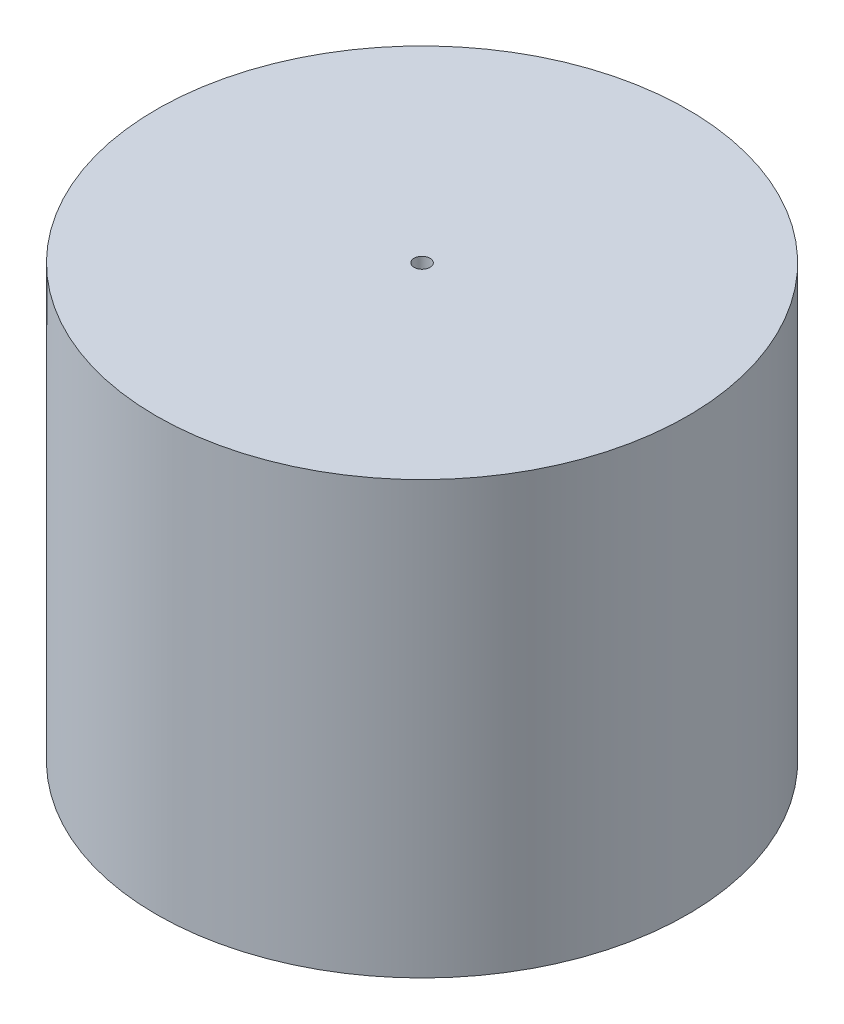
SolidWorks part; units mm, degrees
ref_plane "Front Plane" through (0, 0, 0) normal (0, 0, 1) x (1, 0, 0)
ref_plane "Top Plane" through (0, 0, 0) normal (0, 1, 0) x (1, 0, 0)
ref_plane "Right Plane" through (0, 0, 0) normal (1, 0, 0) x (0, 0, -1)
sketch "Sketch1" plane through (0, 0, 0) normal (0, 1, 0) x (1, 0, 0)
  circle A0 centre (0, 0) radius 20
extrude "Boss-Extrude1" add sketch "Sketch1" against normal blind 7.5
sketch "Sketch2" plane through (0, -7.5, 0) normal (0, -1, 0) x (1, 0, 0)
  circle A0 centre (0, 0) radius 12.5
  circle A1 centre (0, 0) radius 20 construction
  circle A2 centre (0, 0) radius 20
extrude "Boss-Extrude2" add sketch "Sketch2" along normal blind 15
ref_plane "Plane1" through (0, -22.5, 0) normal (0, -1, 0) x (-1, 0, 0)
sketch "Sketch3" plane through (0, -22.5, 0) normal (0, -1, 0) x (1, 0, 0)
  circle A0 centre (0, 0) radius 20 construction
  circle A1 centre (0, 0) radius 20
extrude "Boss-Extrude3" add sketch "Sketch3" along normal blind 10
sketch "Sketch4" plane through (0, -22.5, 0) normal (0, -1, 0) x (-1, 0, 0)
  line L1 (10.1645, 5.4787) -> (0.3376, 11.5421)
  line L2 (0.3376, 11.5421) -> (-9.8269, 6.0634)
  line L3 (-9.8269, 6.0634) -> (-10.1645, -5.4787)
  line L4 (-10.1645, -5.4787) -> (-0.3376, -11.5421)
  line L5 (-0.3376, -11.5421) -> (9.8269, -6.0634)
  line L6 (9.8269, -6.0634) -> (10.1645, 5.4787)
  circle A0 centre (0, 0) radius 10 construction
extrude "Cut-Extrude2" cut sketch "Sketch4" along normal blind 5
sketch "Sketch5" plane through (0, 0, 0) normal (1, 0, 0) x (0, 0, -1)
  line L0 (0, -32.5) -> (0, 0) construction
  line L2 (-20, -32.5) -> (20, -32.5) construction
  line L3 (7.5, -17.5) -> (12.5, -17.5)
  line L5 (-7.5, -17.5) -> (-7.5, -32.5)
  line L6 (-7.5, -32.5) -> (7.5, -32.5)
  line L7 (7.5, -17.5) -> (7.5, -32.5)
  line L8 (-7.5, -17.5) -> (7.5, -32.5) construction
  line L9 (-7.5, -32.5) -> (7.5, -17.5) construction
  line L10 (-12.5, -7.5) -> (12.5, -7.5)
  line L11 (-12.5, -7.5) -> (-12.5, -17.5)
  line L12 (-12.5, -17.5) -> (-7.5, -17.5)
  line L13 (12.5, -7.5) -> (12.5, -17.5)
  line L14 (-12.5, -7.5) -> (12.5, -17.5) construction
  line L15 (-12.5, -17.5) -> (12.5, -7.5) construction
  point P5 (0, -25)
  point P11 (0, -12.5)
  dimension "D1" = 15
  dimension "D2" = 10
  dimension "D3" = 15
  dimension "D4" = 25
extrude "Cut-Extrude3" cut sketch "Sketch5" against normal through all
sketch "Sketch6" plane through (0, -32.5, 0) normal (0, -1, 0) x (1, 0, 0)
  circle A0 centre (0, 0) radius 8
extrude "Cut-Extrude4" cut sketch "Sketch6" against normal blind 5
sketch "Sketch7" plane through (0, -7.5, 0) normal (0, -1, 0) x (1, 0, 0)
  circle A0 centre (0, 0) radius 2.1
extrude "Cut-Extrude5" cut sketch "Sketch7" against normal blind 4.5
sketch "Sketch8" plane through (0, -3, 0) normal (0, -1, 0) x (1, 0, 0)
  circle A0 centre (0, 0) radius 0.6
extrude "Cut-Extrude6" cut sketch "Sketch8" against normal through all
fillet "Fillet1" radius 1.5 1 edges at (0, -7.5, -2.1)
